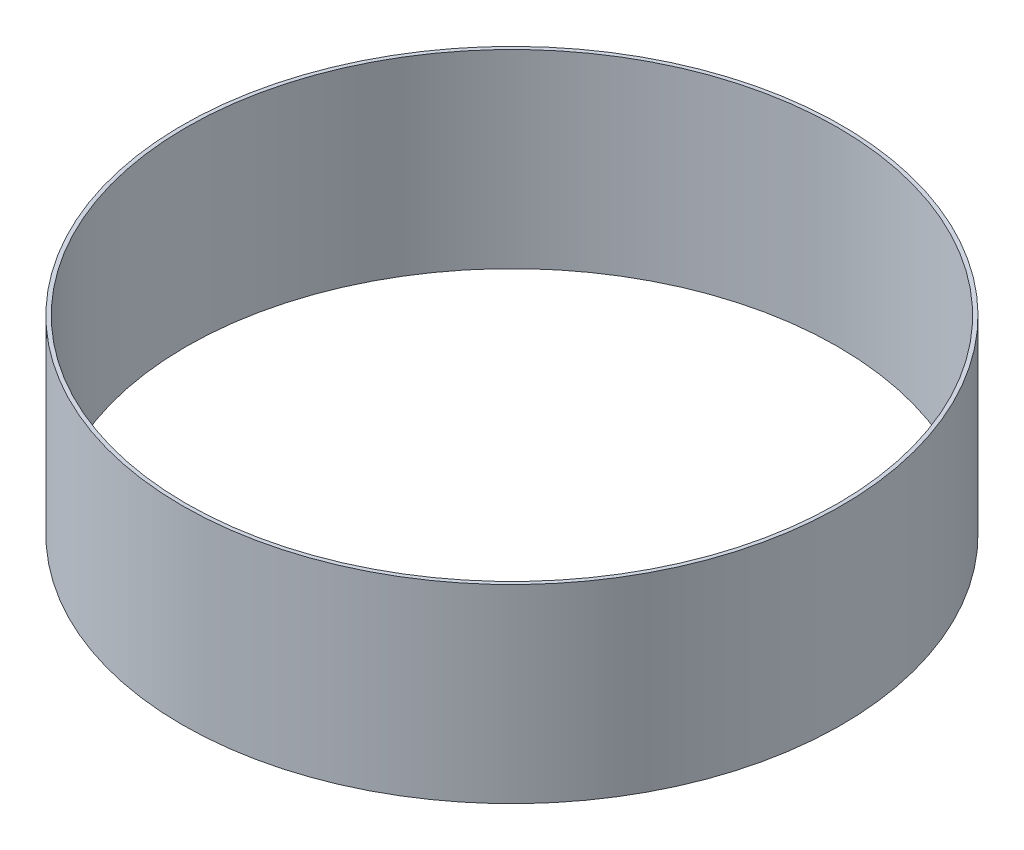
SolidWorks part; units mm, degrees
ref_plane "Front Plane" through (0, 0, 0) normal (0, 0, 1) x (1, 0, 0)
ref_plane "Top Plane" through (0, 0, 0) normal (0, 1, 0) x (1, 0, 0)
ref_plane "Right Plane" through (0, 0, 0) normal (1, 0, 0) x (0, 0, -1)
sketch "Sketch1" plane through (0, 0, 0) normal (0, 0, 1) x (1, 0, 0)
  line L0 (0, 91.7468) -> (0, -48.0019)
  line L1 (130.81, 76.2) -> (132.334, 76.2)
  line L2 (130.81, 76.2) -> (130.81, 0)
  line L3 (130.81, 0) -> (132.334, 0)
  line L4 (132.334, 76.2) -> (132.334, 0)
  point P8 (0, 21.8724)
  dimension "D1" = 1.524
  dimension "D2" = 76.2
  dimension "D3" = 132.334
revolve "Revolve1" add sketch "Sketch1" angle 360 about L0
